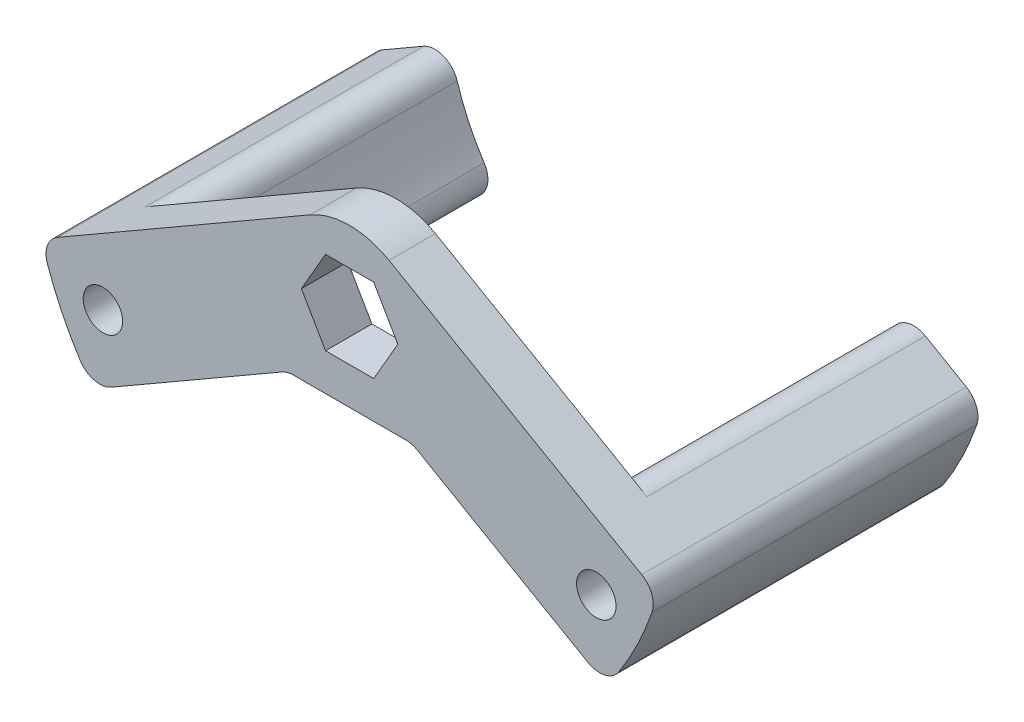
SolidWorks part; units mm, degrees
other "Holder"
material "Nylon 101"
ref_plane "Front" through (0, 0, 0) normal (0, 0, 1) x (1, 0, 0)
ref_plane "Top" through (0, 0, 0) normal (0, 1, 0) x (1, 0, 0)
ref_plane "Right" through (0, 0, 0) normal (1, 0, 0) x (0, 0, -1)
sketch "PlateSke" plane through (0, 0, 0) normal (0, 0, 1) x (1, 0, 0)
  line L0 (-4.8299, -0.8256) -> (-0.85, 1.4722)
  line L1 (1.0392, 0) -> (0.5196, 0.9)
  line L2 (0.5196, 0.9) -> (-0.5196, 0.9)
  line L3 (-0.5196, 0.9) -> (-1.0392, 0)
  line L4 (-1.0392, 0) -> (-0.5196, -0.9)
  line L5 (-0.5196, -0.9) -> (0.5196, -0.9)
  line L6 (0.5196, -0.9) -> (1.0392, 0)
  line L7 (0.85, 1.4722) -> (4.8299, -0.8256)
  circle A0 centre (0, 0) radius 0.9 construction
  arc A1 (0.85, 1.4722) -> (-0.85, 1.4722) centre (0, 0) ccw
  circle A2 centre (0, 0) radius 4.5 construction
  arc A3 (-4.8299, -0.8256) -> (4.8299, -0.8256) centre (0, 0) ccw
  point P12 (0, 1.7)
  dimension "D4" = 9
  dimension "D5" = 4
  dimension "D1" = 1.8
  dimension "D2" = 120
  dimension "D3" = 0.8
extrude "Plate" add sketch "PlateSke" along normal blind 1
sketch "PillarSke" plane through (0, 0, 1) normal (0, 0, 1) x (1, 0, 0)
  line L0 (4.8299, -0.8256) -> (0.85, 1.4722) construction
  line L1 (-0.85, 1.4722) -> (-4.8299, -0.8256) construction
  line L2 (-6.6414, -1.8714) -> (-4.8299, -0.8256)
  line L3 (6.6414, -1.8714) -> (4.8299, -0.8256)
  arc A0 (6.6414, -1.8714) -> (-6.6414, -1.8714) centre (0, 0) cw
  arc A1 (4.8299, -0.8256) -> (-4.8299, -0.8256) centre (0, 0) cw
  arc A2 (-4.8299, -0.8256) -> (4.8299, -0.8256) centre (0, 0) ccw construction
  dimension "D1" = 2
extrude "Pillar" add sketch "PillarSke" against normal blind 7
sketch "CutSke" plane through (0, 0, 1) normal (0, 0, 1) x (1, 0, 0)
  line L0 (-1.3445, -1.7) -> (1.3445, -1.7)
  line L1 (-1.3445, -1.7) -> (-5.5353, -4.1196)
  line L2 (1.3445, -1.7) -> (5.5353, -4.1196)
  line L3 (-0.5196, -0.9) -> (0.5196, -0.9) construction
  line L4 (-0.85, 1.4722) -> (-6.6414, -1.8714) construction
  line L5 (6.6414, -1.8714) -> (0.85, 1.4722) construction
  arc A0 (-6.6414, -1.8714) -> (6.6414, -1.8714) centre (0, 0) ccw construction
  arc A1 (-5.5353, -4.1196) -> (5.5353, -4.1196) centre (0, 0) ccw
  dimension "D1" = 0.8
  dimension "D2" = 2.5
  dimension "D3" = 2.5
extrude "Cut" cut sketch "CutSke" against normal through all
sketch "HoleSke" plane through (0, 0, -6) normal (0, 0, -1) x (-1, 0, 0)
  line L0 (-6.6414, -1.8714) -> (-4.8299, -0.8256) construction
  line L1 (-5.5353, -4.1196) -> (-3.7866, -3.1099) construction
  line L2 (0, 50) -> (0, -50) construction
  line L3 (5.3173, -2.5382) -> (0, 0) construction
  line L4 (0, 0) -> (-5.3173, -2.5382) construction
  circle A0 centre (-5.3173, -2.5382) radius 0.425
  arc A1 (-5.7357, -1.3485) -> (-4.6554, -3.6116) centre (0, 0) ccw construction
  circle A2 centre (5.3173, -2.5382) radius 0.425
  point P10 (-5.3173, -2.5382)
  dimension "D1" = 0.85
  dimension "D2" = 128.966
extrude "Hole" cut sketch "HoleSke" against normal through all
fillet "Fillet" radius 0.5 10 edges at (4.8299, -0.8256, -3) (-4.8299, -0.8256, -3) (6.6414, -1.8714, -2.5) (-6.6414, -1.8714, -2.5) (5.5353, -4.1196, -2.5) (-5.5353, -4.1196, -2.5) (1.3445, -1.7, 0.5) (-1.3445, -1.7, 0.5) (-3.7866, -3.1099, -3) (3.7866, -3.1099, -3)
